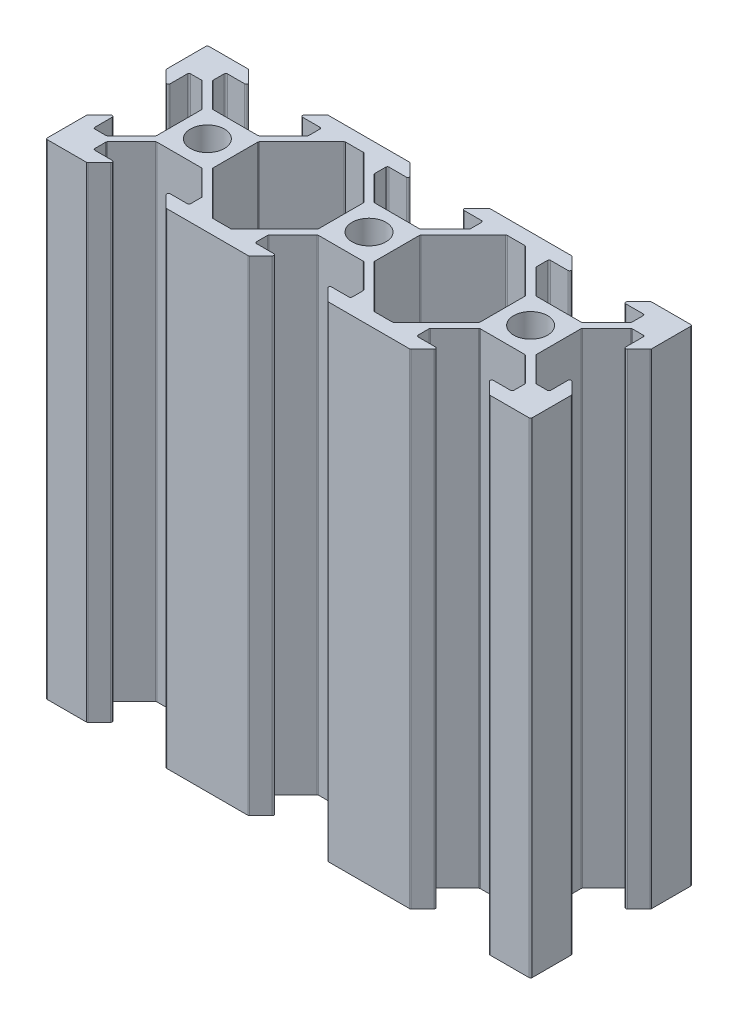
SolidWorks part; units mm, degrees
ref_plane "前视基准面" through (0, 0, 0) normal (0, 0, 1) x (1, 0, 0)
ref_plane "上视基准面" through (0, 0, 0) normal (0, 1, 0) x (1, 0, 0)
ref_plane "右视基准面" through (0, 0, 0) normal (1, 0, 0) x (0, 0, -1)
sketch "草图1" plane through (0, 0, 0) normal (0, 1, 0) x (1, 0, 0)
  line L0 (-25.721, 0) -> (73.7722, 0)
  line L1 (0, 21.255) -> (0, -16.6235)
  line L2 (-10, 21.255) -> (-10, -16.6235)
  line L3 (-25.721, 10) -> (73.7722, 10)
  line L4 (-4.9, 10) -> (-3.1, 8.2)
  line L5 (-3.1, 8.2) -> (-5.9236, 8.2)
  line L6 (-5.9236, 8.2) -> (-5.9236, 6.56)
  line L7 (-5.9236, 6.56) -> (-2.84, 3.4764)
  line L8 (-2.84, 3.4764) -> (2.84, 3.4764)
  line L9 (-10, 10) -> (0, 0) construction
  line L10 (5.9236, 6.56) -> (2.84, 3.4764)
  line L11 (5.9236, 8.2) -> (5.9236, 6.56)
  line L12 (3.1, 8.2) -> (5.9236, 8.2)
  line L13 (4.9, 10) -> (3.1, 8.2)
  line L14 (-10, -4.9) -> (-8.2, -3.1)
  line L15 (-8.2, -3.1) -> (-8.2, -5.9236)
  line L16 (-8.2, -5.9236) -> (-6.56, -5.9236)
  line L17 (-6.56, -5.9236) -> (-3.4764, -2.84)
  line L18 (-3.4764, 2.84) -> (-3.4764, -2.84)
  line L19 (-6.56, 5.9236) -> (-3.4764, 2.84)
  line L20 (-8.2, 5.9236) -> (-6.56, 5.9236)
  line L21 (-8.2, 3.1) -> (-8.2, 5.9236)
  line L22 (-10, 4.9) -> (-8.2, 3.1)
  line L23 (-25.721, -10) -> (73.7722, -10)
  line L24 (4.9, -10) -> (3.1, -8.2)
  line L25 (3.1, -8.2) -> (5.9236, -8.2)
  line L26 (5.9236, -8.2) -> (5.9236, -6.56)
  line L27 (5.9236, -6.56) -> (2.84, -3.4764)
  line L28 (-2.84, -3.4764) -> (2.84, -3.4764)
  line L29 (-5.9236, -6.56) -> (-2.84, -3.4764)
  line L30 (-5.9236, -8.2) -> (-5.9236, -6.56)
  line L31 (-3.1, -8.2) -> (-5.9236, -8.2)
  line L32 (-4.9, -10) -> (-3.1, -8.2)
  line L33 (50, 21.255) -> (50, -16.6235)
  line L34 (20, 21.255) -> (20, -16.6235)
  line L35 (10, 4.9) -> (8.2, 3.1)
  line L36 (8.2, 3.1) -> (8.2, 5.9236)
  line L37 (8.2, 5.9236) -> (6.56, 5.9236)
  line L38 (6.56, 5.9236) -> (3.4764, 2.84)
  line L39 (3.4764, 2.84) -> (3.4764, -2.84)
  line L40 (6.56, -5.9236) -> (3.4764, -2.84)
  line L41 (8.2, -5.9236) -> (6.56, -5.9236)
  line L42 (8.2, -3.1) -> (8.2, -5.9236)
  line L43 (10, -4.9) -> (8.2, -3.1)
  line L44 (15.1, 10) -> (16.9, 8.2)
  line L45 (16.9, 8.2) -> (14.0764, 8.2)
  line L46 (14.0764, 8.2) -> (14.0764, 6.56)
  line L47 (14.0764, 6.56) -> (17.16, 3.4764)
  line L48 (17.16, 3.4764) -> (22.84, 3.4764)
  line L49 (25.9236, 6.56) -> (22.84, 3.4764)
  line L50 (25.9236, 8.2) -> (25.9236, 6.56)
  line L51 (23.1, 8.2) -> (25.9236, 8.2)
  line L52 (24.9, 10) -> (23.1, 8.2)
  line L53 (10, -4.9) -> (11.8, -3.1)
  line L54 (11.8, -3.1) -> (11.8, -5.9236)
  line L55 (11.8, -5.9236) -> (13.44, -5.9236)
  line L56 (13.44, -5.9236) -> (16.5236, -2.84)
  line L57 (16.5236, 2.84) -> (16.5236, -2.84)
  line L58 (13.44, 5.9236) -> (16.5236, 2.84)
  line L59 (11.8, 5.9236) -> (13.44, 5.9236)
  line L60 (11.8, 3.1) -> (11.8, 5.9236)
  line L61 (10, 4.9) -> (11.8, 3.1)
  line L62 (24.9, -10) -> (23.1, -8.2)
  line L63 (23.1, -8.2) -> (25.9236, -8.2)
  line L64 (25.9236, -8.2) -> (25.9236, -6.56)
  line L65 (25.9236, -6.56) -> (22.84, -3.4764)
  line L66 (17.16, -3.4764) -> (22.84, -3.4764)
  line L67 (14.0764, -6.56) -> (17.16, -3.4764)
  line L68 (14.0764, -8.2) -> (14.0764, -6.56)
  line L69 (16.9, -8.2) -> (14.0764, -8.2)
  line L70 (15.1, -10) -> (16.9, -8.2)
  line L71 (30, 4.9) -> (28.2, 3.1)
  line L72 (28.2, 3.1) -> (28.2, 5.9236)
  line L73 (28.2, 5.9236) -> (26.56, 5.9236)
  line L74 (26.56, 5.9236) -> (23.4764, 2.84)
  line L75 (23.4764, 2.84) -> (23.4764, -2.84)
  line L76 (26.56, -5.9236) -> (23.4764, -2.84)
  line L77 (28.2, -5.9236) -> (26.56, -5.9236)
  line L78 (28.2, -3.1) -> (28.2, -5.9236)
  line L79 (30, -4.9) -> (28.2, -3.1)
  line L80 (6.56, 5.9236) -> (8.8364, 8.2)
  line L81 (35.1, 10) -> (36.9, 8.2)
  line L82 (36.9, 8.2) -> (34.0764, 8.2)
  line L83 (34.0764, 8.2) -> (34.0764, 6.56)
  line L84 (34.0764, 6.56) -> (37.16, 3.4764)
  line L85 (37.16, 3.4764) -> (42.84, 3.4764)
  line L86 (45.9236, 6.56) -> (42.84, 3.4764)
  line L87 (45.9236, 8.2) -> (45.9236, 6.56)
  line L88 (43.1, 8.2) -> (45.9236, 8.2)
  line L89 (44.9, 10) -> (43.1, 8.2)
  line L90 (30, -4.9) -> (31.8, -3.1)
  line L91 (31.8, -3.1) -> (31.8, -5.9236)
  line L92 (31.8, -5.9236) -> (33.44, -5.9236)
  line L93 (33.44, -5.9236) -> (36.5236, -2.84)
  line L94 (36.5236, 2.84) -> (36.5236, -2.84)
  line L95 (33.44, 5.9236) -> (36.5236, 2.84)
  line L96 (31.8, 5.9236) -> (33.44, 5.9236)
  line L97 (31.8, 3.1) -> (31.8, 5.9236)
  line L98 (30, 4.9) -> (31.8, 3.1)
  line L99 (44.9, -10) -> (43.1, -8.2)
  line L100 (43.1, -8.2) -> (45.9236, -8.2)
  line L101 (45.9236, -8.2) -> (45.9236, -6.56)
  line L102 (45.9236, -6.56) -> (42.84, -3.4764)
  line L103 (37.16, -3.4764) -> (42.84, -3.4764)
  line L104 (34.0764, -6.56) -> (37.16, -3.4764)
  line L105 (34.0764, -8.2) -> (34.0764, -6.56)
  line L106 (36.9, -8.2) -> (34.0764, -8.2)
  line L107 (35.1, -10) -> (36.9, -8.2)
  line L108 (50, 4.9) -> (48.2, 3.1)
  line L109 (48.2, 3.1) -> (48.2, 5.9236)
  line L110 (48.2, 5.9236) -> (46.56, 5.9236)
  line L111 (46.56, 5.9236) -> (43.4764, 2.84)
  line L112 (43.4764, 2.84) -> (43.4764, -2.84)
  line L113 (46.56, -5.9236) -> (43.4764, -2.84)
  line L114 (48.2, -5.9236) -> (46.56, -5.9236)
  line L115 (48.2, -3.1) -> (48.2, -5.9236)
  line L116 (50, -4.9) -> (48.2, -3.1)
  line L117 (13.44, 5.9236) -> (11.1636, 8.2)
  line L118 (30, 10) -> (40, 0) construction
  line L119 (10, 10) -> (20, 0) construction
  line L120 (8.8364, 8.2) -> (11.1636, 8.2)
  line L121 (8.8364, -8.2) -> (11.1636, -8.2)
  line L122 (6.56, -5.9236) -> (8.8364, -8.2)
  line L123 (13.44, -5.9236) -> (11.1636, -8.2)
  line L124 (26.56, 5.9236) -> (28.8364, 8.2)
  line L125 (28.8364, 8.2) -> (31.1636, 8.2)
  line L126 (33.44, 5.9236) -> (31.1636, 8.2)
  line L127 (26.56, -5.9236) -> (28.8364, -8.2)
  line L128 (28.8364, -8.2) -> (31.1636, -8.2)
  line L129 (33.44, -5.9236) -> (31.1636, -8.2)
  circle A0 centre (0, 0) radius 2.1
  circle A1 centre (20, 0) radius 2.1
  circle A2 centre (40, 0) radius 2.1
  circle A3 centre (20, 0) radius 2.1
  circle A4 centre (40, 0) radius 2.1
  point P22 (0, 3.4764)
  point P37 (-3.4764, 0)
  point P50 (0, -3.4764)
  point P65 (3.4764, 0)
  point P77 (20, 3.4764)
  point P92 (16.5236, 0)
  point P103 (20, -3.4764)
  point P114 (23.4764, 0)
  point P124 (40, 3.4764)
  point P139 (36.5236, 0)
  point P150 (40, -3.4764)
  point P161 (43.4764, 0)
  dimension "D1" = 3
  dimension "D2" = 4.2
  dimension "D3" = 20
  dimension "D6" = 1.8
  dimension "D7" = 1.64
  dimension "D8" = 2.84
  dimension "D9" = 3.1
  dimension "D10" = 45
  dimension "D11" = 0.9
  dimension "D16" = 2
  dimension "D4" = 10
  dimension "D5" = 10
  dimension "D12" = 10
  dimension "D13" = 60
  dimension "D14" = 30
  dimension "D15" = 3
extrude "凸台-拉伸1" add sketch "草图1" along normal blind 60 contours A0 L1 L8 L7 L6 L5 L4 L3 L2 L22 L21 L20 L19 L18 L0 | A0 L0 L18 L17 L16 L15 L14 L2 L23 L32 L31 L30 L29 L28 L1 | A1 L0 L57 L56 L123 L121 L122 L40 L39 A0 L1 L28 L27 L26 L25 L24 L23 L70 L69 L68 L67 L66 L34 | A1 L34 L48 L47 L46 L45 L44 L3 L13 L12 L11 L10 L8 L1 A0 L0 L39 L38 L80 L120 L117 L58 L57 | A2 L0 L112 L111 L110 L109 L108 L33 L3 L89 L88 L87 L86 L85 L84 L83 L82 L81 L52 L51 L50 L49 L48 L34 A1 L75 L74 L124 L125 L126 L95 L94 | A2 L0 L94 L93 L129 L128 L127 L76 L75 A1 L34 L66 L65 L64 L63 L62 L23 L107 L106 L105 L104 L103 L102 L101 L100 L99 L33 L116 L115 L114 L113 L112
fillet "圆角1" radius 0.2 100 edges at (8.8364, 30, 8.2) (11.1636, 30, 8.2) (16.5236, 30, 2.84) (16.5236, 30, -2.84) (11.1636, 30, -8.2) (8.8364, 30, -8.2) (3.4764, 30, -2.84) (3.4764, 30, 2.84) (28.8364, 30, 8.2) (31.1636, 30, 8.2) (36.5236, 30, 2.84) (36.5236, 30, -2.84) (31.1636, 30, -8.2) (28.8364, 30, -8.2) (23.4764, 30, -2.84) (23.4764, 30, 2.84) (46.56, 30, 5.9236) (48.2, 30, 5.9236) (48.2, 30, 3.1) (50, 30, 4.9) (50, 30, 10) (44.9, 30, 10) (43.1, 30, 8.2) (45.9236, 30, 8.2) (45.9236, 30, 6.56) (42.84, 30, 3.4764) (37.16, 30, 3.4764) (34.0764, 30, 6.56) (34.0764, 30, 8.2) (36.9, 30, 8.2) (35.1, 30, 10) (24.9, 30, 10) (23.1, 30, 8.2) (25.9236, 30, 8.2) (25.9236, 30, 6.56) (22.84, 30, 3.4764) (17.16, 30, 3.4764) (14.0764, 30, 6.56) (14.0764, 30, 8.2) (16.9, 30, 8.2) (15.1, 30, 10) (4.9, 30, 10) (3.1, 30, 8.2) (5.9236, 30, 8.2) (5.9236, 30, 6.56) (2.84, 30, 3.4764) (-2.84, 30, 3.4764) (-5.9236, 30, 6.56) (-5.9236, 30, 8.2) (-3.1, 30, 8.2) (-4.9, 30, 10) (-10, 30, 10) (-10, 30, 4.9) (-8.2, 30, 3.1) (-8.2, 30, 5.9236) (-6.56, 30, 5.9236) (-3.4764, 30, 2.84) (-3.4764, 30, -2.84) (-6.56, 30, -5.9236) (-8.2, 30, -5.9236) (-8.2, 30, -3.1) (-10, 30, -4.9) (-10, 30, -10) (-4.9, 30, -10) (-3.1, 30, -8.2) (-5.9236, 30, -8.2) (-5.9236, 30, -6.56) (-2.84, 30, -3.4764) (2.84, 30, -3.4764) (5.9236, 30, -6.56) (5.9236, 30, -8.2) (3.1, 30, -8.2) (4.9, 30, -10) (15.1, 30, -10) (16.9, 30, -8.2) (14.0764, 30, -8.2) (14.0764, 30, -6.56) (17.16, 30, -3.4764) (22.84, 30, -3.4764) (25.9236, 30, -6.56) (25.9236, 30, -8.2) (23.1, 30, -8.2) (24.9, 30, -10) (35.1, 30, -10) (36.9, 30, -8.2) (34.0764, 30, -8.2) (34.0764, 30, -6.56) (37.16, 30, -3.4764) (42.84, 30, -3.4764) (45.9236, 30, -6.56) (45.9236, 30, -8.2) (43.1, 30, -8.2) (44.9, 30, -10) (50, 30, -4.9) (48.2, 30, -3.1) (48.2, 30, -5.9236) (46.56, 30, -5.9236) (43.4764, 30, -2.84) (43.4764, 30, 2.84) (50, 30, -10)
